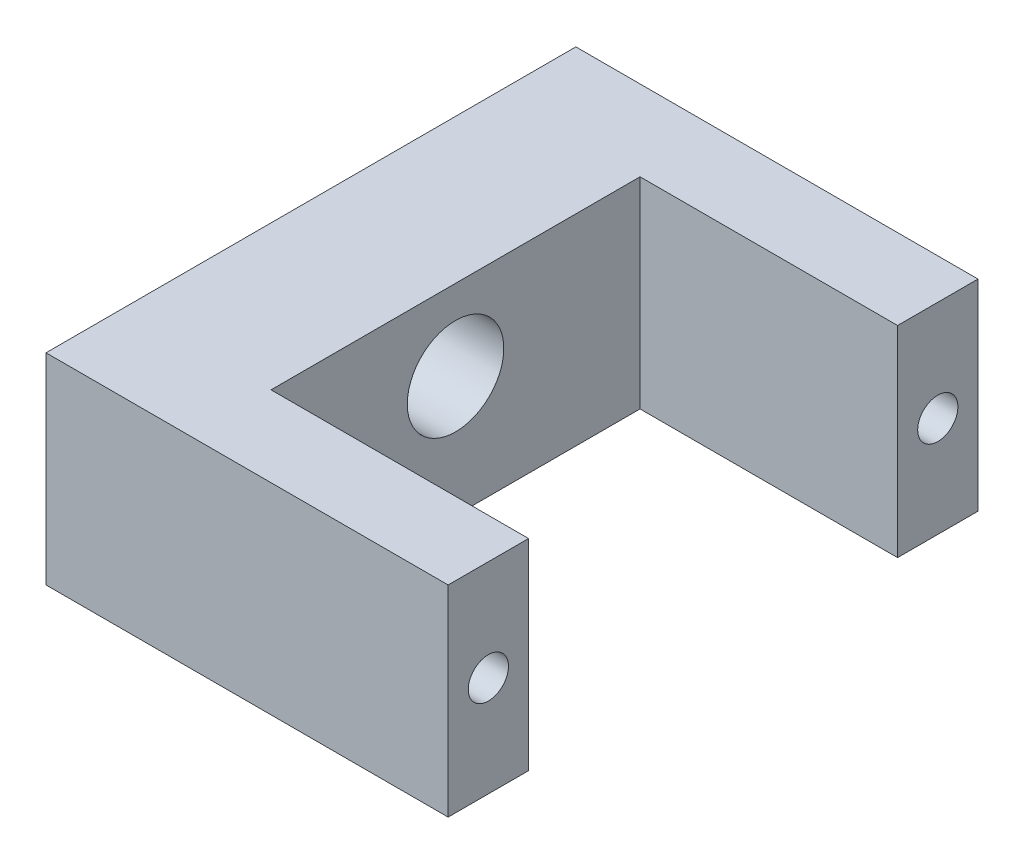
SolidWorks part; units mm, degrees
ref_plane "Ön Düzlem" through (0, 0, 0) normal (0, 0, 1) x (1, 0, 0)
ref_plane "Üst Düzlem" through (0, 0, 0) normal (0, 1, 0) x (1, 0, 0)
ref_plane "Sağ Düzlem" through (0, 0, 0) normal (1, 0, 0) x (0, 0, -1)
sketch "Çizim1" plane through (0, 0, 0) normal (0, 1, 0) x (1, 0, 0)
  line L0 (0, 0) -> (0, 32.94)
  line L1 (0, 32.94) -> (25, 32.94)
  line L2 (25, 32.94) -> (25, 27.94)
  line L3 (25, 27.94) -> (8.99, 27.94)
  line L4 (8.99, 27.94) -> (8.99, 5)
  line L5 (8.99, 5) -> (25, 5)
  line L6 (25, 5) -> (25, 0)
  line L7 (25, 0) -> (0, 0)
  dimension "D1" = 22.94
  dimension "D2" = 5
  dimension "D3" = 16.01
  dimension "D4" = 25
extrude "Yükseklik-Ekstrüzyon1" add sketch "Çizim1" along normal mid plane 12.5
sketch "Çizim2" plane through (25, 0, 0) normal (1, 0, 0) x (0, 0, -1)
  line L1 (0, 6.25) -> (5, 6.25) construction
  circle A0 centre (2.5, 0) radius 1.25
  point P6 (2.5, 6.25)
  dimension "D1" = 2.5
extrude "Kes-Ekstrüzyon1" cut sketch "Çizim2" against normal blind 12.5
ref_plane "Düzlem1" through (0, 0, -16.47) normal (0, 0, 1) x (1, 0, 0)
mirror "Aynalama1" about plane through (0, 0, -16.47) normal (0, 0, 1) of "Kes-Ekstrüzyon1"
sketch "Çizim4" plane through (0, 0, 0) normal (-1, 0, 0) x (0, 0, 1)
  line L0 (-32.94, 6.25) -> (-32.94, -6.25) construction
  line L2 (-32.94, 6.25) -> (0, 6.25) construction
  circle A0 centre (-16.47, 1.25) radius 3
  dimension "D1" = 6
  dimension "D2" = 16.47
  dimension "D3" = 5
extrude "Kes-Ekstrüzyon2" cut sketch "Çizim4" against normal blind 10
